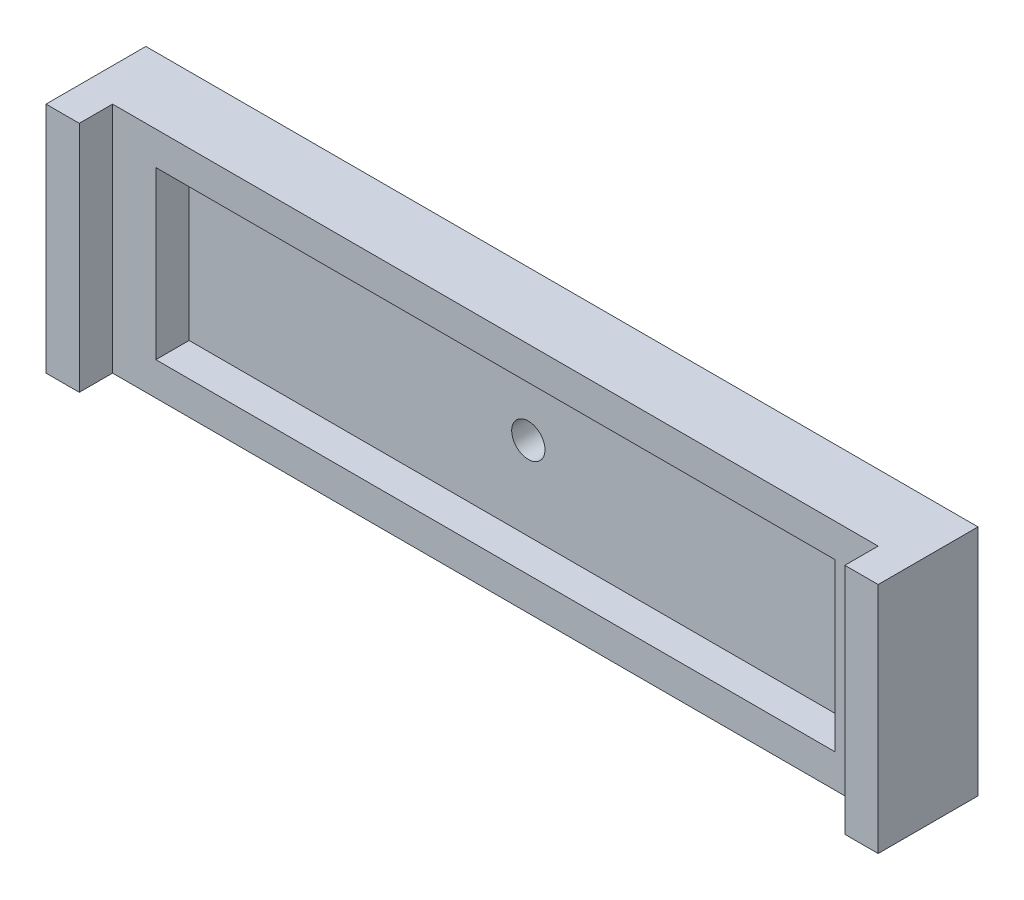
SolidWorks part; units mm, degrees
ref_plane "Front Plane" through (0, 0, 0) normal (0, 0, 1) x (1, 0, 0)
ref_plane "Top Plane" through (0, 0, 0) normal (0, 1, 0) x (1, 0, 0)
ref_plane "Right Plane" through (0, 0, 0) normal (1, 0, 0) x (0, 0, -1)
sketch "Sketch1" plane through (0, 0, 0) normal (0, 1, 0) x (1, 0, 0)
  line L0 (-125, 0) -> (125, 0)
  line L1 (125, 0) -> (125, 30)
  line L2 (125, 30) -> (119.5, 30)
  line L3 (-125, 30) -> (-125, 0)
  line L4 (-119.5, 30) -> (-125, 30)
  line L5 (95.5, 30) -> (-95.5, 30)
  line L6 (-119.5, 42) -> (-119.5, 30)
  line L7 (-95.5, 42) -> (-95.5, 30)
  line L8 (95.5, 42) -> (95.5, 30)
  line L9 (119.5, 42) -> (119.5, 30)
  arc A1 (-95.5, 42) -> (-119.5, 42) centre (-107.5, 42) ccw
  arc A2 (119.5, 42) -> (95.5, 42) centre (107.5, 42) ccw
  circle A3 centre (107.5, 42) radius 5
  circle A4 centre (-107.5, 42) radius 5
  dimension "D5" = 24
  dimension "D7" = 10
  dimension "D1" = 30
  dimension "D2" = 250
  dimension "D3" = 125
  dimension "D4" = 215
  dimension "D6" = 107.5
extrude "Boss-Extrude1" add sketch "Sketch1" along normal blind 70
sketch "Sketch2" plane through (0, 0, 0) normal (0, 0, 1) x (1, 0, 0)
  line L8 (-125, 0) -> (125, 0)
  line L9 (125, 0) -> (125, 70)
  line L10 (125, 70) -> (-125, 70)
  line L11 (-125, 70) -> (-125, 0)
  line L12 (-125, 0) -> (125, 0)
  line L13 (125, 0) -> (125, 70)
  line L14 (125, 70) -> (-125, 70)
  line L15 (-125, 70) -> (-125, 0)
  dimension "D1" = 0
sketch "Sketch3" plane through (-125, 0, 0) normal (-1, 0, 0) x (0, 0, 1)
  line L0 (-30, 0) -> (-80, 0)
  line L1 (-80, 0) -> (-80, 30)
  line L2 (-80, 30) -> (-30, 30)
  line L3 (-30, 70) -> (-30, 0) construction
  line L4 (-30, 0) -> (-30, 30)
  dimension "D1" = 30
  dimension "D2" = 50
extrude "Cut-Extrude1" cut sketch "Sketch3" against normal through all contours L4 L2 L1 L0
sketch "Sketch6" plane through (0, 0, 0) normal (0, 0, 1) x (1, 0, 0)
  line L0 (-115, 10) -> (115, 10)
  line L1 (115, 10) -> (115, 60)
  line L2 (115, 60) -> (-115, 60)
  line L3 (-115, 60) -> (-115, 10)
  line L4 (-125, 0) -> (125, 0)
  line L5 (125, 0) -> (125, 70)
  line L6 (125, 70) -> (-125, 70)
  line L7 (-125, 70) -> (-125, 0)
  line L8 (-125, 0) -> (125, 0) construction
  line L9 (125, 0) -> (125, 70) construction
  line L10 (125, 70) -> (-125, 70) construction
  line L11 (-125, 70) -> (-125, 0) construction
  dimension "D1" = 0
  dimension "D2" = 10
extrude "Cut-Extrude2" cut sketch "Sketch6" against normal blind 20 contours L0 L1 L2 L3
sketch "Sketch7" plane through (0, 0, -20) normal (0, 0, 1) x (1, 0, 0)
  line L0 (-0.0942, 35) -> (115, 35)
  line L4 (-115, 60) -> (-115, 10)
  line L5 (-115, 10) -> (115, 10)
  line L6 (115, 10) -> (115, 60)
  line L7 (115, 60) -> (-115, 60)
  line L8 (-115, 60) -> (-115, 10)
  line L9 (-115, 10) -> (115, 10)
  line L10 (115, 10) -> (115, 60)
  line L11 (115, 60) -> (-115, 60)
  circle A0 centre (-0.0942, 35) radius 5
  dimension "D2" = 10
  dimension "D1" = 0
extrude "Cut-Extrude3" cut sketch "Sketch7" against normal through all
sketch "Sketch8" plane through (125, 0, 0) normal (1, 0, 0) x (0, 0, -1)
  line L0 (30, 70) -> (64.8307, 70)
  line L1 (64.8307, 70) -> (64.8307, 0)
  line L2 (64.8307, 0) -> (30, 0)
  line L3 (30, 0) -> (30, 70)
extrude "Cut-Extrude4" cut sketch "Sketch8" against normal through all
sketch "Sketch9" plane through (0, 70, 0) normal (0, 1, 0) x (1, 0, 0)
  line L0 (-115, 0) -> (-115, 10)
  line L1 (-125, 0) -> (125, 0) construction
  line L2 (-115, 10) -> (115, 10)
  line L3 (115, 10) -> (115, 0)
  line L4 (125, 0) -> (-125, 0) construction
  line L5 (115, 0) -> (-115, 0)
  line L6 (-125, 30) -> (-125, 0) construction
  line L7 (125, 0) -> (125, 30) construction
  dimension "D1" = 10
  dimension "D2" = 10
  dimension "D3" = 10
extrude "Cut-Extrude5" cut sketch "Sketch9" against normal through all
sketch "Sketch10" plane through (0, 0, -20) normal (0, 0, 1) x (1, 0, 0)
  line L2 (0, 60) -> (0, 10) construction
  line L6 (-102, 10) -> (-102, 60)
  line L11 (115, 60) -> (115, 10)
  line L12 (115, 10) -> (102, 10)
  line L13 (-115, 10) -> (115, 10) construction
  line L14 (102, 10) -> (102, 60)
  line L15 (115, 60) -> (-115, 60) construction
  line L16 (102, 60) -> (115, 60)
  line L17 (-115, 10) -> (-102, 10)
  line L18 (-115, 60) -> (-115, 10)
  line L19 (-115, 60) -> (-115, 10)
  line L20 (-115, 10) -> (115, 10)
  line L21 (115, 10) -> (115, 60)
  line L22 (115, 60) -> (-115, 60)
  line L23 (-115, 60) -> (-115, 10) construction
  line L24 (-115, 10) -> (115, 10) construction
  line L25 (115, 10) -> (115, 60) construction
  line L26 (115, 60) -> (-115, 60) construction
  line L27 (-102, 60) -> (-115, 60)
  dimension "D1" = 0
  dimension "D2" = 13
extrude "Boss-Extrude4" add sketch "Sketch10" along normal blind 10
